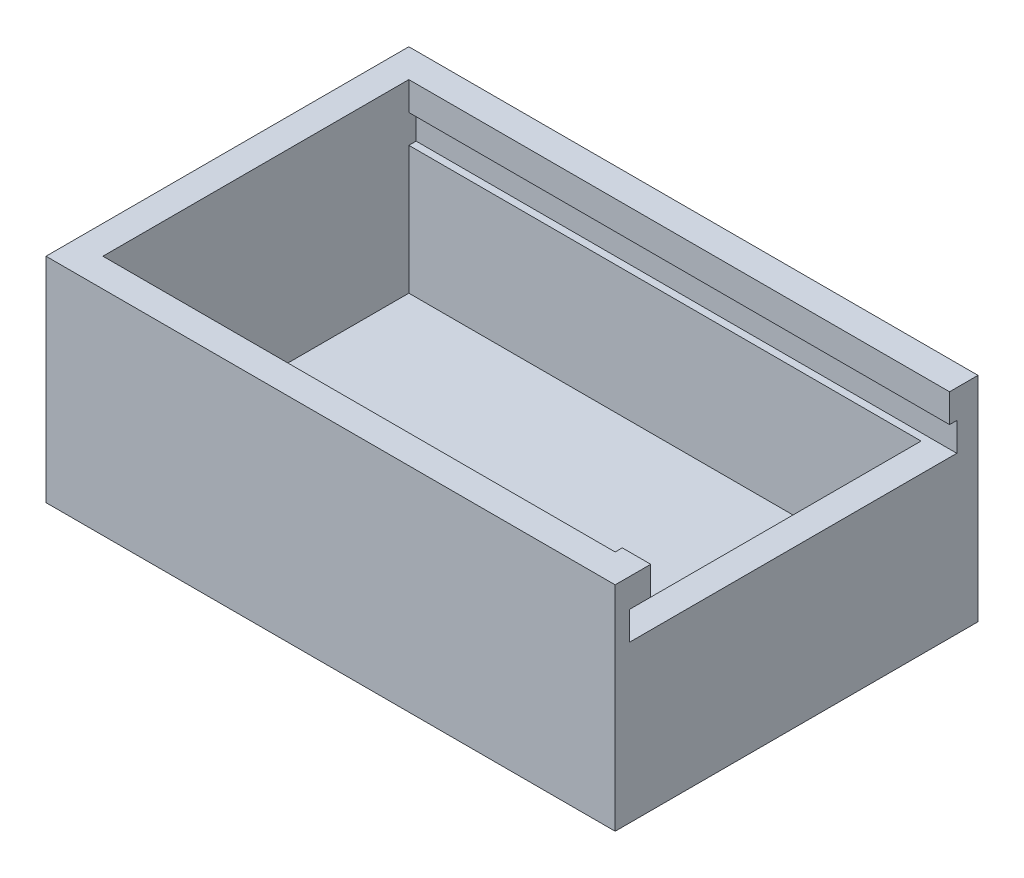
SolidWorks part; units mm, degrees
ref_plane "Front Plane" through (0, 0, 0) normal (0, 0, 1) x (1, 0, 0)
ref_plane "Top Plane" through (0, 0, 0) normal (0, 1, 0) x (1, 0, 0)
ref_plane "Right Plane" through (0, 0, 0) normal (1, 0, 0) x (0, 0, -1)
sketch "Sketch1" plane through (0, 0, 0) normal (0, 1, 0) x (1, 0, 0)
  line L1 (-20, -12.75) -> (20, -12.75)
  line L2 (-20, -12.75) -> (-20, 12.75)
  line L3 (-20, 12.75) -> (20, 12.75)
  line L4 (20, -12.75) -> (20, 12.75)
  line L5 (-20, -12.75) -> (20, 12.75) construction
  line L6 (-20, 12.75) -> (20, -12.75) construction
  point P0 (0, 0)
  dimension "D1" = 40
  dimension "D2" = 25.5
extrude "Boss-Extrude1" add sketch "Sketch1" along normal blind 15
shell "Shell1" thickness 2
sketch "Sketch2" plane through (20, 0, 0) normal (1, 0, 0) x (0, 0, -1)
  line L1 (-10.25, 15) -> (10.75, 15)
  line L2 (-10.25, 15) -> (-10.25, 11)
  line L3 (-10.25, 11) -> (10.75, 11)
  line L4 (10.75, 15) -> (10.75, 11)
  line L5 (12.75, 15) -> (12.75, 0) construction
  dimension "D1" = 21
  dimension "D2" = 4
  dimension "D3" = 2
extrude "Cut-Extrude1" cut sketch "Sketch2" against normal blind 2
sketch "Sketch3" plane through (20, 0, 0) normal (1, 0, 0) x (0, 0, -1)
  line L11 (-10.25, 11) -> (10.75, 11) construction
  line L12 (-11.75, 11) -> (11.26, 11)
  line L13 (-11.75, 11) -> (-11.75, 13)
  line L14 (-11.75, 13) -> (11.26, 13)
  line L15 (11.26, 11) -> (11.26, 13)
  line L16 (-12.75, 15) -> (-12.75, 0) construction
  dimension "D1" = 2
  dimension "D2" = 23.01
  dimension "D3" = 1
extrude "Cut-Extrude2" cut sketch "Sketch3" against normal blind 38
equation "\"box width\"= 25mm"
equation "\"fit width\"= 23mm"
equation "\"lid thickness\"= 2mm"
equation "\"track width\" = \"fit width\" + 0.00635mm"
equation "\"groove height\" = \"lid thickness\" + 0.003175mm"
equation "\"track offset\"= ( \"box width\" - \"track width\" ) / 2"
